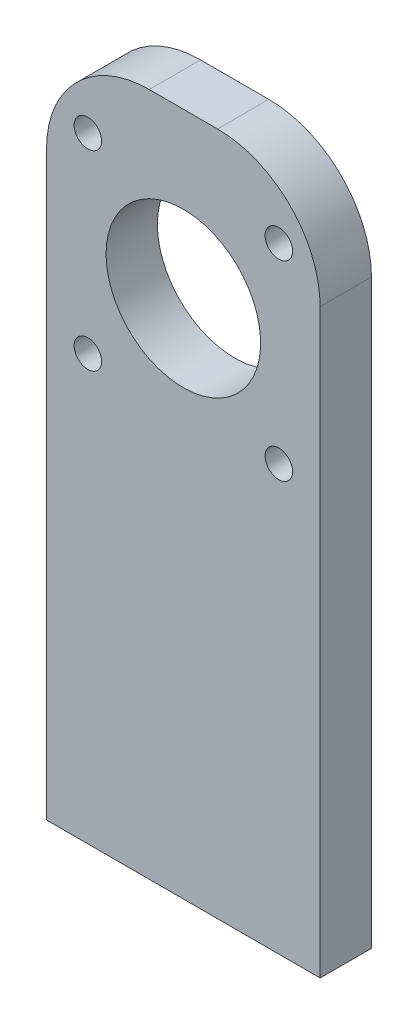
SolidWorks part; units mm, degrees
ref_plane "Front Plane" through (0, 0, 0) normal (0, 0, 1) x (1, 0, 0)
ref_plane "Top Plane" through (0, 0, 0) normal (0, 1, 0) x (1, 0, 0)
ref_plane "Right Plane" through (0, 0, 0) normal (1, 0, 0) x (0, 0, -1)
sketch "Sketch2" plane through (0, 0, 0) normal (0, 0, 1) x (1, 0, 0)
  line L1 (0, 0) -> (50.8, 0)
  line L2 (0, 0) -> (0, 127)
  line L3 (0, 127) -> (50.8, 127)
  line L4 (50.8, 0) -> (50.8, 127)
  circle A0 centre (25.4, 96.5708) radius 14.351
  circle A1 centre (43.1292, 114.3) radius 2.5527
  circle A2 centre (7.6708, 114.3) radius 2.5527
  circle A3 centre (7.6708, 78.8416) radius 2.5527
  circle A4 centre (43.1292, 78.8416) radius 2.5527
  point P8 (0, 0)
  dimension "D4" = 28.702
  dimension "D5" = 5.1054
  dimension "D7" = 5.1054
  dimension "D8" = 5.1054
  dimension "D9" = 5.1054
  dimension "D3" = 35.4584
  dimension "D6" = 35.4584
  dimension "D12" = 12.7
  dimension "D1" = 127
  dimension "D2" = 50.8
  dimension "D10" = 35.4584
  dimension "D11" = 35.4584
  dimension "D13" = 17.7292
  dimension "D14" = 17.7292
  dimension "D15" = 17.7292
extrude "Boss-Extrude3" add sketch "Sketch2" along normal blind 9.525
fillet "Fillet1" radius 19.05 1 edges at (50.8, 127, 4.7625)
fillet "Fillet4" radius 19.05 1 edges at (0, 127, 4.7625)
